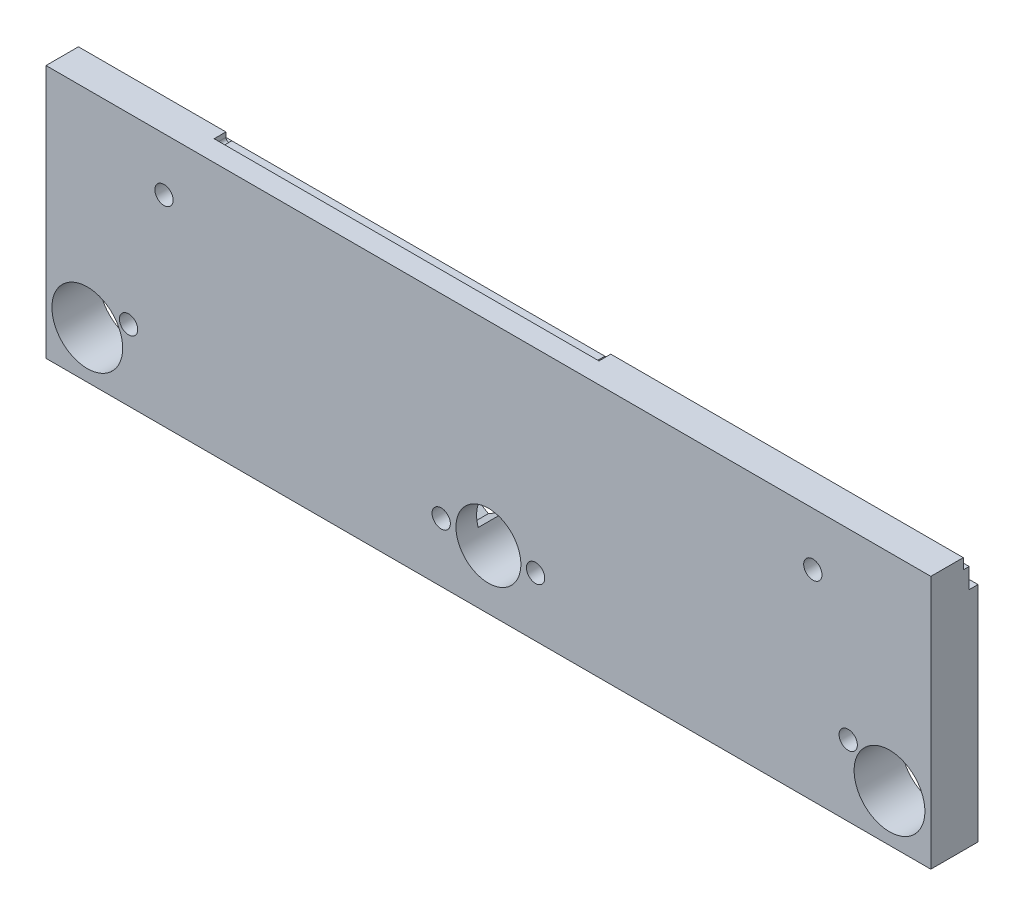
SolidWorks part; units mm, degrees
ref_plane "前视基准面" through (0, 0, 0) normal (0, 0, 1) x (1, 0, 0)
ref_plane "上视基准面" through (0, 0, 0) normal (0, 1, 0) x (1, 0, 0)
ref_plane "右视基准面" through (0, 0, 0) normal (1, 0, 0) x (0, 0, -1)
sketch "草图2" plane through (0, 0, 0) normal (0, 0, 1) x (1, 0, 0)
  line L0 (0, 0) -> (150, 0)
  line L2 (150, 0) -> (150, 43)
  line L3 (150, 43) -> (0, 43)
  line L5 (0, 43) -> (0, 0)
  line L6 (75, 43) -> (75, 0) construction
  circle A0 centre (7, 8) radius 6
  circle A1 centre (75, 10) radius 4.05
  circle A2 centre (143, 8) radius 6
  dimension "D3" = 8
  dimension "D5" = 10
  dimension "D9" = 12
  dimension "D10" = 12
  dimension "D11" = 8.1
  dimension "D1" = 43
  dimension "D2" = 150
  dimension "D4" = 7
  dimension "D6" = 7
  dimension "D7" = 8
extrude "凸台-拉伸1" add sketch "草图2" along normal blind 8
sketch "草图3" plane through (0, 0, 8) normal (0, 0, 1) x (1, 0, 0)
  line L0 (16.088, 8) -> (31.4805, 8) construction
  line L1 (7, 8) -> (7, 16.8386) construction
  line L2 (143, 8) -> (143, 16.5917) construction
  line L3 (0, 0) -> (150, 0) construction
  circle A2 centre (23, 8) radius 2.55
  circle A3 centre (127, 8) radius 2.55
  dimension "D4" = 5.1
  dimension "D5" = 5.1
  dimension "D1" = 8
  dimension "D2" = 16
  dimension "D3" = 16
extrude "切除-拉伸1" [suppressed] cut sketch "草图3" against normal through all
sketch "草图4" plane through (150, 0, 0) normal (1, 0, 0) x (0, 0, -1)
  line L2 (-1.5, 41.2) -> (-2.5, 41.2)
  line L3 (-2.5, 41.2) -> (-2.5, 43)
  line L4 (-8, 43) -> (0, 43) construction
  line L5 (-2.5, 43) -> (0, 43)
  line L6 (-1.5, 41.2) -> (-1.5, 37.8)
  line L7 (-1.5, 37.8) -> (0, 37.8)
  line L8 (0, 37.8) -> (0, 43)
  dimension "D1" = 3.4
  dimension "D2" = 2.5
  dimension "D3" = 1.5
  dimension "D4" = 1.8
extrude "切除-拉伸2" cut sketch "草图4" against normal through all
sketch "草图5" plane through (0, 0, 8) normal (0, 0, 1) x (1, 0, 0)
  line L0 (75, 10) -> (91.5376, 10) construction
  circle A0 centre (75, 10) radius 8 construction
  circle A1 centre (83, 10) radius 1.55
  circle A2 centre (67, 10) radius 1.55
  dimension "D1" = 3.1
  dimension "D2" = 3.1
  dimension "D3" = 16
extrude "切除-拉伸3" cut sketch "草图5" against normal through all
sketch "草图7" [suppressed] plane through (0, 0, 0) normal (0, 0, -1) x (-1, 0, 0)
  line L0 (-40, 12) -> (-40, -8.3696) construction
  line L1 (-23, 10) -> (-23, -2.3368) construction
  line L2 (200000, 0) -> (-200044.4821, 0) construction
  line L6 (-27.05, 10) -> (-27.05, 2.5)
  line L7 (-29.55, 0) -> (-16.45, 0)
  line L8 (-18.95, 2.5) -> (-18.95, 10)
  line L9 (-23, 8) -> (-23, 15.9045) construction
  line L13 (0, -200000) -> (0, 200028.3185) construction
  line L14 (-57, 8) -> (-57, 15.9045) construction
  line L15 (-57, 10) -> (-57, -2.3368) construction
  line L16 (-61.05, 2.5) -> (-61.05, 10)
  line L17 (-50.45, 0) -> (-63.55, 0)
  line L18 (-52.95, 10) -> (-52.95, 2.5)
  arc A1 (-18.95, 10) -> (-27.05, 10) centre (-23, 10) ccw
  arc A4 (-29.55, 0) -> (-27.05, 2.5) centre (-29.55, 2.5) ccw
  arc A5 (-18.95, 2.5) -> (-16.45, 0) centre (-16.45, 2.5) ccw
  arc A7 (-61.05, 2.5) -> (-63.55, 0) centre (-63.55, 2.5) cw
  arc A8 (-50.45, 0) -> (-52.95, 2.5) centre (-50.45, 2.5) cw
  arc A9 (-61.05, 10) -> (-52.95, 10) centre (-57, 10) cw
  dimension "D1" = 40
  dimension "D4" = 8.1
  dimension "D7" = 2.5
  dimension "D8" = 2.5
  dimension "D3" = 10
extrude "切除-拉伸4" [suppressed] cut sketch "草图7" against normal blind 6
sketch "草图8" plane through (0, 0, 0) normal (0, 0, -1) x (-1, 0, 0)
  line L0 (-75, 10) -> (-92.3165, 10) construction
  line L1 (-75, 20) -> (-75, 35.6562) construction
  line L2 (-65.5, 12.85) -> (-84.5, 12.85)
  line L3 (-84.5, 7.15) -> (-65.5, 7.15)
  line L5 (-150, 0) -> (-150, 37.8) construction
  line L6 (-80.15, 8.3546) -> (-80.15, 11.6454)
  line L7 (-80.15, 11.6454) -> (-83, 13.2909)
  line L8 (-83, 13.2909) -> (-85.85, 11.6454)
  line L9 (-85.85, 11.6454) -> (-85.85, 8.3546)
  line L10 (-85.85, 8.3546) -> (-83, 6.7091)
  line L11 (-83, 6.7091) -> (-80.15, 8.3546)
  line L12 (-69.85, 8.3546) -> (-67, 6.7091)
  line L13 (-67, 6.7091) -> (-64.15, 8.3546)
  line L14 (-64.15, 8.3546) -> (-64.15, 11.6454)
  line L15 (-64.15, 11.6454) -> (-67, 13.2909)
  line L16 (-67, 13.2909) -> (-69.85, 11.6454)
  line L17 (-69.85, 11.6454) -> (-69.85, 8.3546)
  line L19 (0, 0) -> (-150, 0) construction
  line L20 (0, 37.8) -> (0, 0) construction
  arc A0 (-65.5, 7.15) -> (-65.5, 12.85) centre (-65.5, 10) ccw
  arc A1 (-84.5, 12.85) -> (-84.5, 7.15) centre (-84.5, 10) ccw
  circle A2 centre (-83, 10) radius 2.85 construction
  circle A3 centre (-67, 10) radius 2.85 construction
  dimension "D1" = 5.7
  dimension "D2" = 9.5
  dimension "D3" = 9.5
  dimension "D4" = 10
  dimension "D5" = 5.7
  dimension "D6" = 75
extrude "切除-拉伸5" cut sketch "草图8" against normal blind 4.5 contours L9 L10 L11 L6 L7 L8 | L17 L12 L13 L14 L15 L16
sketch "草图11" plane through (0, 0, 0) normal (0, 0, -1) x (-1, 0, 0)
  line L0 (0, 43) -> (-150, 43) construction
  line L1 (-150, 0) -> (-150, 37.8) construction
  line L3 (-40, 20) -> (-40, 13.5744) construction
  line L4 (-28.772, 34) -> (-45.9396, 34) construction
  line L5 (0, 37.8) -> (0, 0) construction
  circle A0 centre (-130, 34) radius 1.55
  circle A1 centre (-20, 34) radius 1.55
  point P23 (-40, 20)
  dimension "D1" = 3.1
  dimension "D2" = 3.1
  dimension "D3" = 20
  dimension "D4" = 20
  dimension "D5" = 9
sketch "草图20" plane through (0, 0, 0) normal (0, 0, -1) x (-1, 0, 0)
  circle A0 centre (-75, 10) radius 5.5
  dimension "D1" = 11
extrude "切除-拉伸7" cut sketch "草图11" against normal through all contours A0 | A1
sketch "草图19" plane through (0, 0, 2.5) normal (0, 0, -1) x (-1, 0, 0)
  line L0 (0, 43) -> (-150, 43) construction
  line L1 (-25, 43) -> (-90.2479, 43)
  line L2 (-25, 43) -> (-25, 42.2)
  line L3 (-26, 42.2) -> (-89.2479, 42.2)
  line L4 (-90.2479, 43) -> (-90.2479, 42.2)
  line L6 (-75, 10) -> (-75, 2.3588) construction
  line L7 (0, 41.2) -> (-150, 41.2) construction
  line L8 (-56.3335, 41.7) -> (-52.9089, 41.7) construction
  line L9 (-90.2479, 1028.5823) -> (-90.2479, 42.2) construction
  line L10 (-60, 1028.5823) -> (-60, 41.7) construction
  line L11 (-90.2479, 41.7) -> (-90.2479, -973.3) construction
  line L12 (-60, 41.7) -> (-60, -973.3) construction
  arc A3 (-90.2479, 42.2) -> (-89.2479, 42.2) centre (-89.7479, 42.2) ccw
  arc A6 (-26, 42.2) -> (-25, 42.2) centre (-25.5, 42.2) ccw
  dimension "D3" = 1
  dimension "D4" = 1
  dimension "D5" = 30.2479
  dimension "D6" = 15
  dimension "D2" = 0.8
  dimension "D1" = 0.5
extrude "切除-拉伸11" cut sketch "草图19" against normal blind 2
sketch "草图22" plane through (0, 0, 0) normal (0, 0, -1) x (-1, 0, 0)
  line L0 (-136, 0) -> (-136, 37.8) construction
  line L2 (0, 37.8) -> (-150, 37.8) construction
  line L3 (-150, 12) -> (0, 12) construction
  line L4 (-150, 0) -> (-150, 37.8) construction
  line L6 (0, 0) -> (-150, 0) construction
  line L7 (-75, 41.2) -> (-75, 0) construction
  line L8 (0, 41.2) -> (-150, 41.2) construction
  line L9 (0, 37.8) -> (0, 0) construction
  circle A0 centre (-136, 12) radius 1.55
  circle A1 centre (-14, 12) radius 1.55
  point P2 (0, 0)
  point P3 (0, 0)
  point P10 (0, 0)
  dimension "D3" = 3.1
  dimension "D1" = 12
  dimension "D2" = 14
extrude "切除-拉伸13" cut sketch "草图22" against normal through all
extrude "切除-拉伸14" cut sketch "草图20" against normal through all
